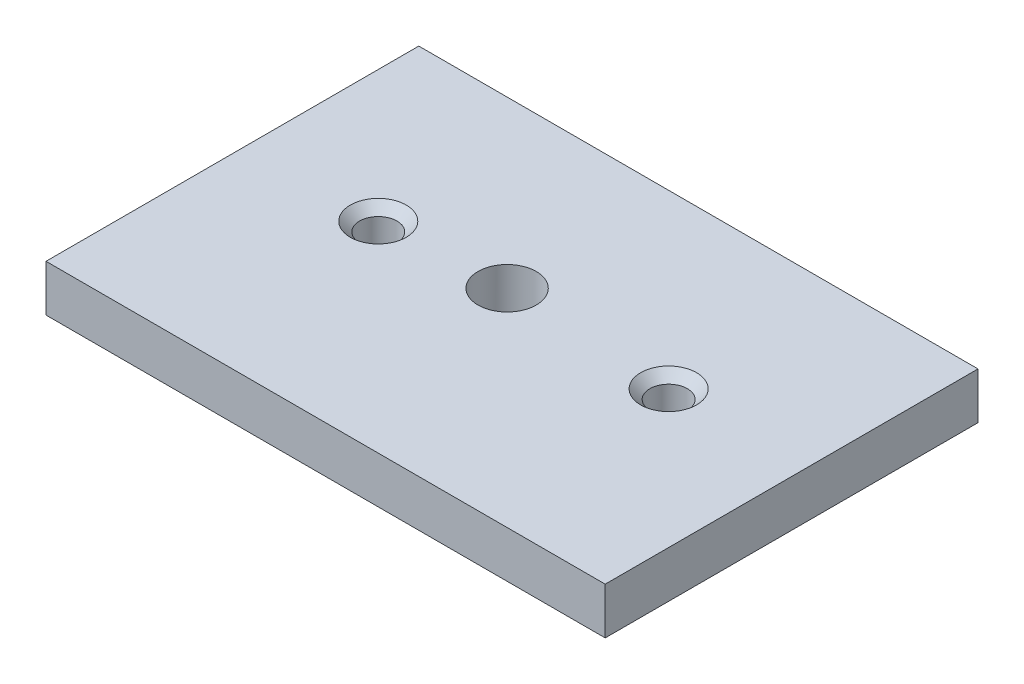
SolidWorks part; units mm, degrees
material "6061 Alloy"
ref_plane "Front Plane" through (0, 0, 0) normal (0, 0, 1) x (1, 0, 0)
ref_plane "Top Plane" through (0, 0, 0) normal (0, 1, 0) x (1, 0, 0)
ref_plane "Right Plane" through (0, 0, 0) normal (1, 0, 0) x (0, 0, -1)
sketch "Sketch1" plane through (0, 0, 0) normal (0, 1, 0) x (1, 0, 0)
  line L1 (0, 0) -> (76.2, 0)
  line L2 (0, 0) -> (0, 50.8)
  line L3 (0, 50.8) -> (76.2, 50.8)
  line L4 (76.2, 0) -> (76.2, 50.8)
  dimension "D1" = 50.8
  dimension "D2" = 76.2
extrude "Boss-Extrude1" add sketch "Sketch1" along normal blind 6.35
hole_wizard "1/4-20 Tapped Hole1" positions "Sketch2" profile "Sketch3" tap size "1/4-20" standard "ANSI Inch" end condition through all
sketch "Sketch2" plane through (0, 6.35, 0) normal (0, 1, 0) x (1, 0, 0)
  point P0 (17.9055, 27.3723)
  point P2 (57.4702, 27.3723)
sketch "Sketch3" plane through (17.9055, 6.35, -27.3723) normal (1, 0, 0) x (0, 0, 1)
  line L0 (0, 0) -> (0, 6.35)
  line L1 (0, 6.35) -> (2.5527, 6.35)
  line L2 (2.5527, 6.35) -> (2.5527, 1.2573)
  line L3 (2.5527, 1.2573) -> (3.81, 0)
  line L5 (3.81, 0) -> (0, 0)
  line L6 (-2.5527, 1.2573) -> (-3.81, 0) construction
  line L11 (0, -6.35) -> (0, 107.95) construction
  dimension "Thru Tap Drill Dia." = 5.1054
  dimension "Thru Tap Drill Depth" = 6.35
  dimension "Near C'Sink Dia." = 7.62
  dimension "Near C'Sink Angle" = 90
cosmetic thread "Hole Thread1" parameters "D2"=6.35
cosmetic thread "Hole Thread2" parameters "D2"=6.35
hole_wizard "3/8-16 Tapped Hole1" positions "Sketch6" profile "Sketch7" tap size "3/8-16" standard "ANSI Inch" end condition up to next
sketch "Sketch6" plane through (0, 6.35, 0) normal (0, 1, 0) x (1, 0, 0)
  point P0 (34.5998, 28.2343)
sketch "Sketch7" plane through (34.5998, 6.35, -28.2343) normal (1, 0, 0) x (0, 0, 1)
  line L0 (0, 0) -> (0, 6.35)
  line L1 (0, 6.35) -> (3.9687, 6.35)
  line L2 (3.9687, 6.35) -> (3.9687, 0)
  line L5 (3.9687, 0) -> (0, 0)
  line L11 (0, -6.35) -> (0, 107.95) construction
  dimension "Thru Tap Drill Dia." = 7.9375
  dimension "Thru Tap Drill Depth" = 6.35
cosmetic thread "Hole Thread3" parameters "D2"=9.525
